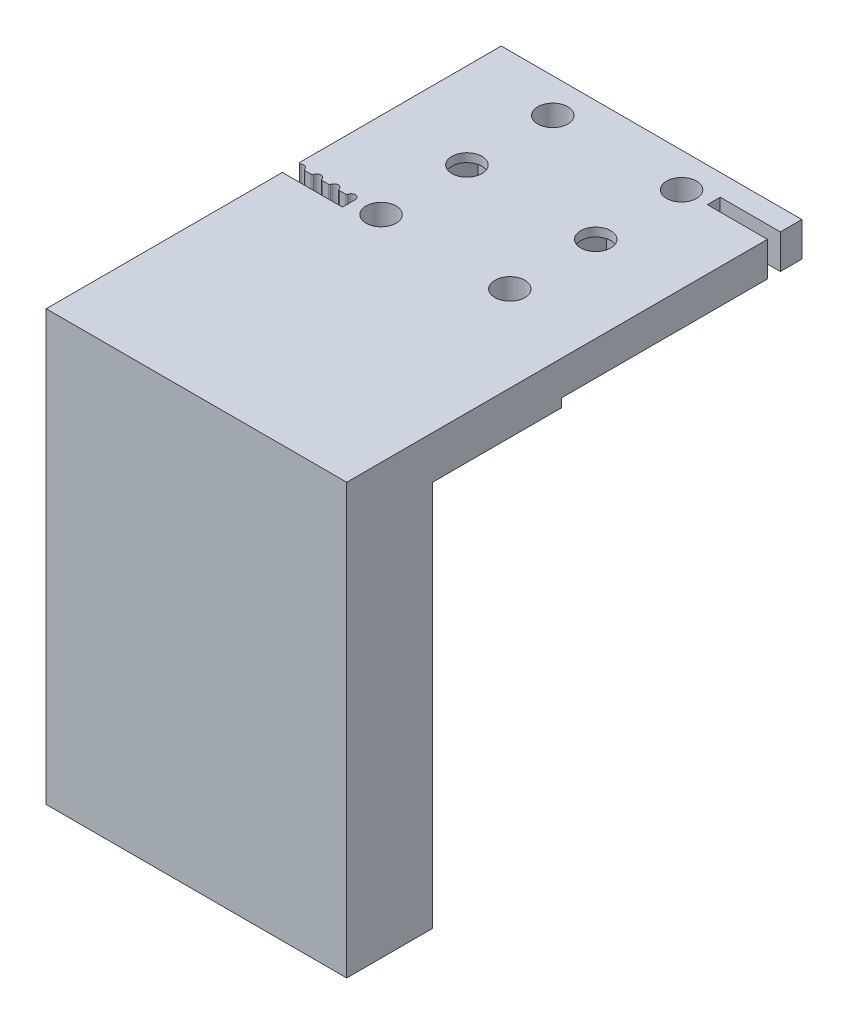
SolidWorks part; units mm, degrees
material "ABS"
ref_plane "Front Plane" through (0, 0, 0) normal (0, 0, 1) x (1, 0, 0)
ref_plane "Top Plane" through (0, 0, 0) normal (0, 1, 0) x (1, 0, 0)
ref_plane "Right Plane" through (0, 0, 0) normal (1, 0, 0) x (0, 0, -1)
sketch "Sketch1" plane through (0, 0, 0) normal (0, 1, 0) x (1, 0, 0)
  line L1 (-17.5, -14) -> (17.5, -14)
  line L2 (-17.5, -14) -> (-17.5, 14)
  line L3 (-17.5, 14) -> (17.5, 14)
  line L4 (17.5, -14) -> (17.5, 14)
  line L5 (-17.5, -14) -> (17.5, 14) construction
  line L6 (-17.5, 14) -> (17.5, -14) construction
  point P0 (0, 0)
  dimension "D1" = 28
  dimension "D2" = 35
extrude "Boss-Extrude1" add sketch "Sketch1" along normal blind 4
sketch "Sketch2" plane through (0, 4, 0) normal (0, 1, 0) x (1, 0, 0)
  line L0 (-17.5, -14) -> (17.5, -14) construction
  line L1 (-17.5, 14) -> (-17.5, -14) construction
  line L2 (-17.5, -14) -> (17.5, -14) construction
  line L3 (17.5, 14) -> (-17.5, 14) construction
  circle A0 centre (-7.5, -10) radius 1.75
  circle A1 centre (-7.5, 10) radius 1.75
  circle A2 centre (7.5, -10) radius 1.75
  circle A3 centre (7.5, 10) radius 1.75
  dimension "D1" = 3.5
  dimension "D2" = 3.5
  dimension "D5" = 3.5
  dimension "D8" = 3.5
  dimension "D3" = 20
  dimension "D4" = 4
  dimension "D6" = 15
  dimension "D7" = 10
  dimension "D9" = 15
  dimension "D10" = 4
  dimension "D11" = 4
extrude "Cut-Extrude1" cut sketch "Sketch2" against normal through all
sketch "Sketch3" plane through (0, 0, 14) normal (0, 0, 1) x (1, 0, 0)
  line L0 (17.5, 4) -> (17.5, 0) construction
  line L1 (-17.5, 4) -> (17.5, 4)
  line L2 (-17.5, 4) -> (-17.5, -46)
  line L3 (-17.5, -46) -> (17.5, -46)
  line L4 (17.5, 4) -> (17.5, -46)
  dimension "D1" = 50
extrude "Boss-Extrude2" add sketch "Sketch3" along normal blind 25
sketch "Sketch18" plane through (0, 4, 0) normal (0, 1, 0) x (1, 0, 0)
  line L0 (-17.5, -10) -> (-10.5, -10)
  line L1 (-17.5, 19) -> (-17.5, -24) construction
  line L2 (-10.5, -10) -> (-10.5, -11.5)
  line L3 (-10.5, -11.5) -> (-17.5, -11.5)
  line L4 (-17.5, -11.5) -> (-17.5, -10)
  line L5 (17.5, 10) -> (10.5, 10)
  line L6 (17.5, -24) -> (17.5, 19) construction
  line L7 (10.5, 10) -> (10.5, 11.5)
  line L8 (10.5, 11.5) -> (17.5, 11.5)
  line L9 (17.5, 11.5) -> (17.5, 10)
  circle A0 centre (-7.5, -10) radius 1.75 construction
  circle A1 centre (7.5, 10) radius 1.75 construction
  dimension "D4" = 3
  dimension "D1" = 0
  dimension "D2" = 3
  dimension "D3" = 1.5
  dimension "D5" = 0
  dimension "D6" = 1.5
extrude "Cut-Extrude14" cut sketch "Sketch18" against normal through all
sketch "Sketch19" plane through (0, 4, 0) normal (0, 1, 0) x (1, 0, 0)
  line L0 (-17.5, 14) -> (-17.5, -10) construction
  line L1 (17.5, -39) -> (17.5, 10) construction
  circle A0 centre (-7.5, 0) radius 1.75
  circle A1 centre (7.5, 0) radius 1.75
  dimension "D3" = 3.5
  dimension "D4" = 3.5
  dimension "D1" = 10
  dimension "D2" = 10
extrude "Cut-Extrude15" cut sketch "Sketch19" against normal through all
sketch "Sketch20" plane through (0, 0, 0) normal (0, -1, 0) x (1, 0, 0)
  line L1 (10.9641, 0) -> (9.2321, 3)
  line L2 (9.2321, 3) -> (5.7679, 3)
  line L3 (5.7679, 3) -> (4.0359, 0)
  line L4 (4.0359, 0) -> (5.7679, -3)
  line L5 (5.7679, -3) -> (9.2321, -3)
  line L6 (9.2321, -3) -> (10.9641, 0)
  line L7 (-10.9641, 0) -> (-9.2321, -3)
  line L8 (-9.2321, -3) -> (-5.7679, -3)
  line L9 (-5.7679, -3) -> (-4.0359, 0)
  line L10 (-4.0359, 0) -> (-5.7679, 3)
  line L11 (-5.7679, 3) -> (-9.2321, 3)
  line L12 (-9.2321, 3) -> (-10.9641, 0)
  circle A0 centre (7.5, 0) radius 3 construction
  circle A1 centre (-7.5, 0) radius 3 construction
  dimension "D1" = 6
  dimension "D2" = 6
extrude "Cut-Extrude16" cut sketch "Sketch20" against normal blind 3
sketch "Sketch21" plane through (0, 4, 0) normal (0, 1, 0) x (1, 0, 0)
  line L0 (-10.5, -10) -> (-17.5, -10) construction
  circle A0 centre (-17, -10) radius 0.5
  dimension "D1" = 1
extrude "Cut-Extrude17" cut sketch "Sketch21" against normal blind 4
pattern_linear "LPattern2" count 4 spacing 2 along (1, 0, 0) of "Cut-Extrude17"
fillet "Fillet2" radius 0.15 7 edges at (-16.5, 2, 10) (-12.5, 2, 10) (-13.5, 2, 10) (-14.5, 2, 10) (-15.5, 2, 10) (-11.5, 2, 10) (-17.5, 2, 10)
sketch "Sketch22" plane through (-17.5, 0, 0) normal (-1, 0, 0) x (0, 0, 1)
  line L1 (14, -46) -> (29, -46)
  line L2 (14, -46) -> (14, -1)
  line L3 (14, -1) -> (29, -1)
  line L4 (29, -46) -> (29, -1)
  dimension "D1" = 15
  dimension "D2" = 45
extrude "Cut-Extrude18" cut sketch "Sketch22" against normal through all
